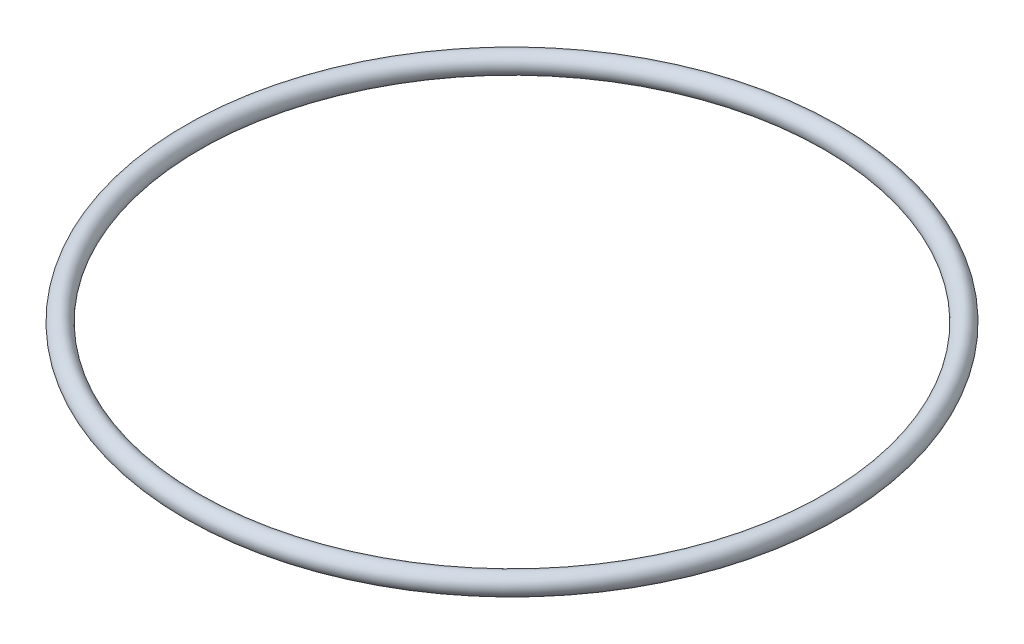
SolidWorks part; units mm, degrees
ref_plane "Alzado" through (0, 0, 0) normal (0, 0, 1) x (1, 0, 0)
ref_plane "Planta" through (0, 0, 0) normal (0, 1, 0) x (1, 0, 0)
ref_plane "Vista lateral" through (0, 0, 0) normal (1, 0, 0) x (0, 0, -1)
sketch "Croquis1" plane through (0, 0, 0) normal (0, 0, 1) x (1, 0, 0)
  line L0 (55, 0) -> (-55, 0) construction
  line L1 (0, -55) -> (0, 55) construction
  line L2 (0, 0) -> (0, 100) construction
  circle A0 centre (400, 0) radius 12.5
  dimension "D1" = 25
  dimension "D2" = 400
  dimension "D3" = 100
revolve "Revolución1" add sketch "Croquis1" angle 360 about L2
